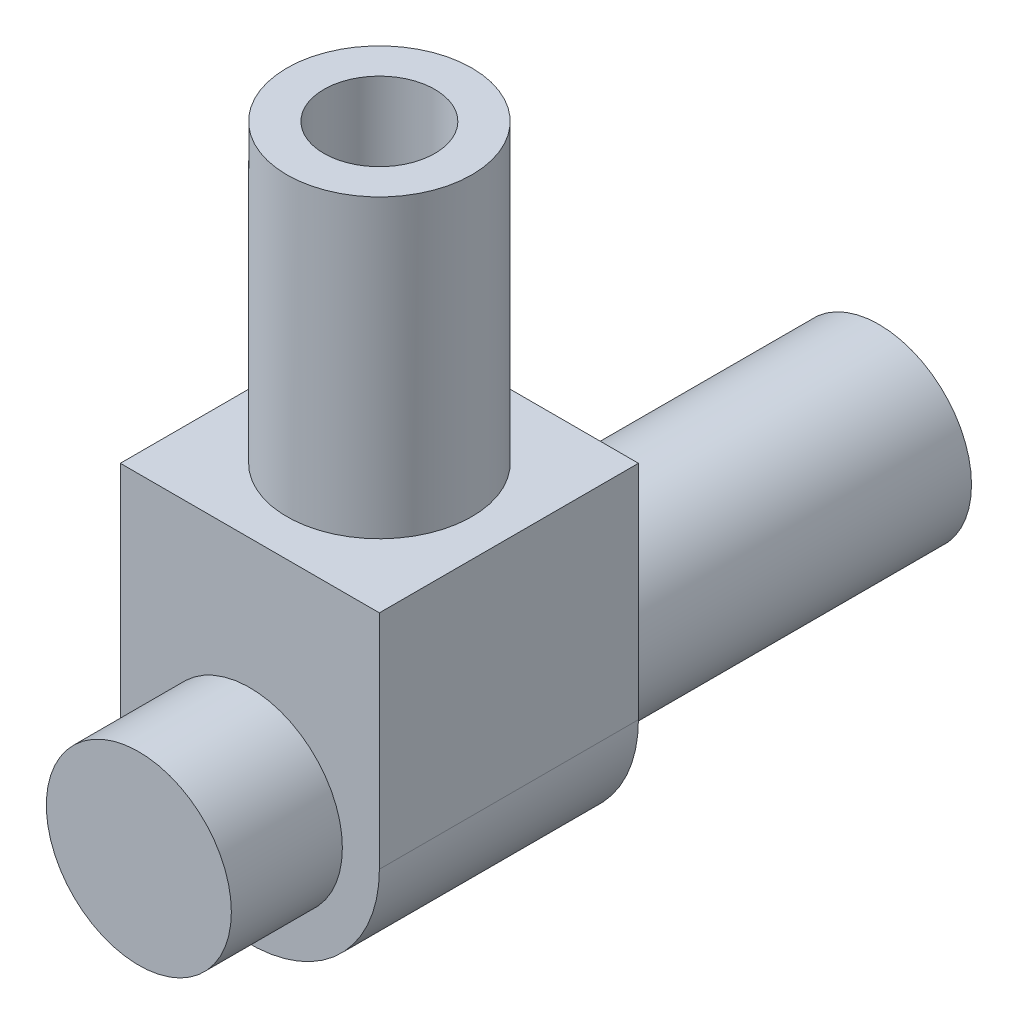
SolidWorks part; units mm, degrees
ref_plane "前基準面" through (0, 0, 0) normal (0, 0, 1) x (1, 0, 0)
ref_plane "上基準面" through (0, 0, 0) normal (0, 1, 0) x (1, 0, 0)
ref_plane "右基準面" through (0, 0, 0) normal (1, 0, 0) x (0, 0, -1)
sketch "草圖1" plane through (0, 0, 0) normal (0, 0, 1) x (1, 0, 0)
  line L0 (-3.5, 0) -> (-3.5, 6)
  line L1 (-3.5, 6) -> (3.5, 6)
  line L2 (3.5, 6) -> (3.5, 0)
  arc A0 (-3.5, 0) -> (3.5, 0) centre (0, 0) ccw
  dimension "D1" = 3.5
  dimension "D2" = 6
extrude "伸長1" add sketch "草圖1" along normal blind 7
sketch "草圖3" plane through (0, 0, 7) normal (0, 0, 1) x (1, 0, 0)
  circle A0 centre (0, 0) radius 2.5
  dimension "D1" = 5
extrude "伸長2" add sketch "草圖3" along normal blind 3
sketch "草圖4" plane through (0, 0, 0) normal (0, 0, -1) x (-1, 0, 0)
  circle A0 centre (0, 0) radius 2.5
  dimension "D1" = 5
extrude "伸長3" add sketch "草圖4" along normal blind 10
sketch "草圖5" plane through (0, 6, 0) normal (0, 1, 0) x (1, 0, 0)
  line L0 (3.5, 0) -> (-3.5, -7) construction
  circle A0 centre (0, -3.5) radius 1.5
  circle A1 centre (0, -3.5) radius 2.5
  dimension "D1" = 3
  dimension "D2" = 5
extrude "伸長5" add sketch "草圖5" along normal blind 8
sketch "草圖6" plane through (0, 6, 0) normal (0, 1, 0) x (1, 0, 0)
  circle A1 centre (0, -3.5) radius 1.5
  circle A2 centre (0, -3.5) radius 1.5
  dimension "D1" = 0
extrude "伸長6" cut sketch "草圖6" against normal through all
